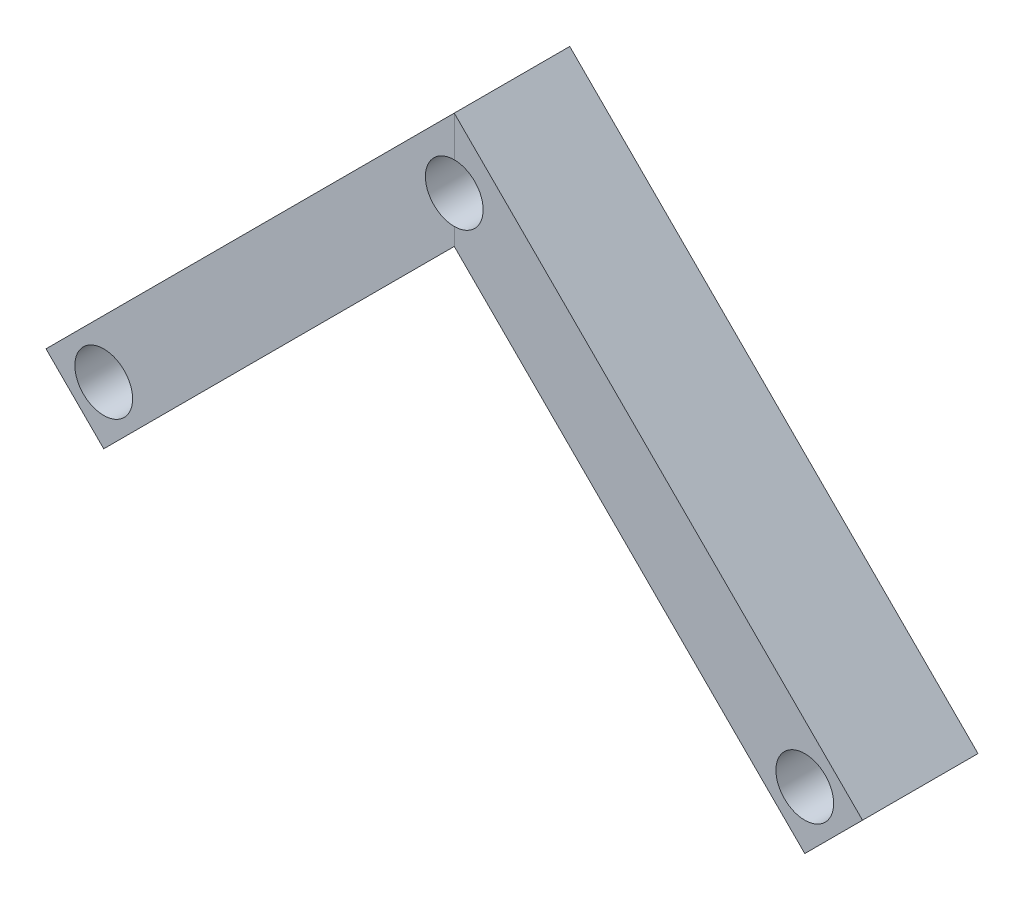
SolidWorks part; units mm, degrees
ref_plane "Front Plane" through (0, 0, 0) normal (0, 0, 1) x (1, 0, 0)
ref_plane "Top Plane" through (0, 0, 0) normal (0, 1, 0) x (1, 0, 0)
ref_plane "Right Plane" through (0, 0, 0) normal (1, 0, 0) x (0, 0, -1)
sketch "Sketch1" plane through (0, 0, 0) normal (0, 0, 1) x (1, 0, 0)
  line L0 (0, 0) -> (70.7107, 70.7107)
  line L1 (70.7107, 70.7107) -> (141.4214, 0)
  line L2 (0, 0) -> (29.6913, 0) construction
  point P6 (0, 0)
  dimension "D1" = 100
sketch "Sketch2" plane through (0, 0, 0) normal (1, 0, 0) x (0, 0, -1)
  line L1 (-10, -10) -> (10, -10)
  line L2 (-10, -10) -> (-10, 10)
  line L3 (-10, 10) -> (10, 10)
  line L4 (10, -10) -> (10, 10)
  line L5 (-10, -10) -> (10, 10) construction
  line L6 (-10, 10) -> (10, -10) construction
  point P0 (0, 0)
  dimension "D1" = 20
  dimension "D2" = 20
sweep "Sweep1" add profiles "Sketch2" path "Sketch1"
sketch "Sketch4" plane through (0, 0, 0) normal (0, 0, 1) x (1, 0, 0)
  line L0 (0, 10) -> (10, 0)
  line L1 (0, -10) -> (70.7107, 60.7107) construction
  line L2 (10, 0) -> (0, -10)
  line L3 (0, -10) -> (0, 10)
  line L4 (70.7107, 80.7107) -> (70.7107, 7.6606) construction
  line L5 (70.7107, 80.7107) -> (70.7107, 60.7107) construction
  line L6 (141.4214, -10) -> (141.4214, 10)
  line L7 (131.4214, 0) -> (141.4214, -10)
  line L8 (141.4214, 10) -> (131.4214, 0)
extrude "Cut-Extrude2" cut sketch "Sketch4" against normal through all both and the other way through all
sketch "Sketch3" plane through (0, 0, 0) normal (0, 0, 1) x (1, 0, 0)
  line L0 (70.7107, 80.7107) -> (70.7107, 60.7107) construction
  line L1 (10, 10) -> (5, 15) construction
  line L2 (0, 10) -> (70.7107, 80.7107) construction
  line L3 (70.7107, 80.7107) -> (70.7107, 5) construction
  line L5 (10, 10) -> (15, 5) construction
  line L6 (10, 10) -> (5, 5) construction
  line L7 (10, 0) -> (0, 10) construction
  line L8 (10, 0) -> (70.7107, 60.7107) construction
  circle A0 centre (70.7107, 68.7107) radius 5
  circle A1 centre (10, 10) radius 5
  circle A2 centre (131.4214, 10) radius 5
  point P6 (70.7107, 60.7107)
  dimension "D1" = 8
  dimension "D2" = 10
  dimension "D3" = 10
extrude "Cut-Extrude1" cut sketch "Sketch3" against normal through all both and the other way through all
